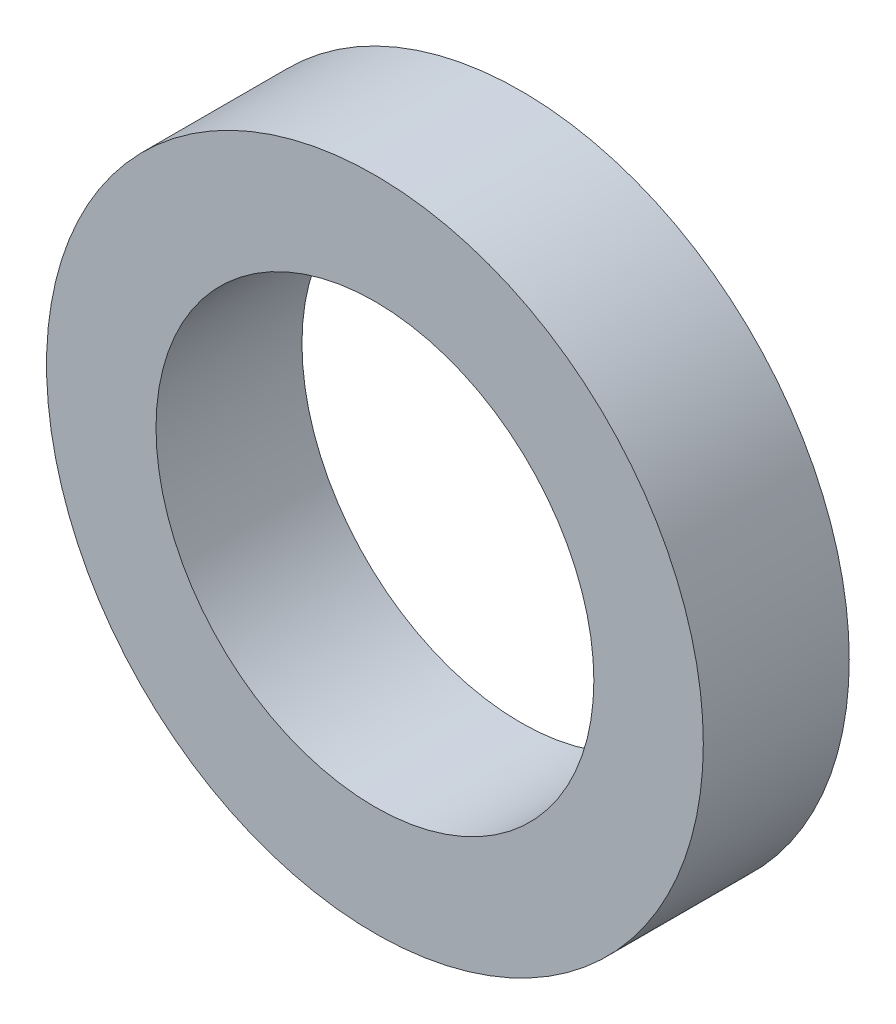
SolidWorks part; units mm, degrees
material "AISI 304"
ref_plane "Front" through (0, 0, 0) normal (0, 0, 1) x (1, 0, 0)
ref_plane "Top" through (0, 0, 0) normal (0, 1, 0) x (1, 0, 0)
ref_plane "Right" through (0, 0, 0) normal (1, 0, 0) x (0, 0, -1)
sketch "Sketch1" plane through (0, 0, 0) normal (0, 0, 1) x (1, 0, 0)
  circle A0 centre (0, 0) radius 9
  dimension "D1" = 18
extrude "Boss-Extrude1" add sketch "Sketch1" along normal blind 4
sketch "Sketch2" plane through (0, 0, 4) normal (0, 0, 1) x (1, 0, 0)
  circle A0 centre (0, 0) radius 6
  dimension "D1" = 12
extrude "Cut-Extrude1" cut sketch "Sketch2" against normal through all
